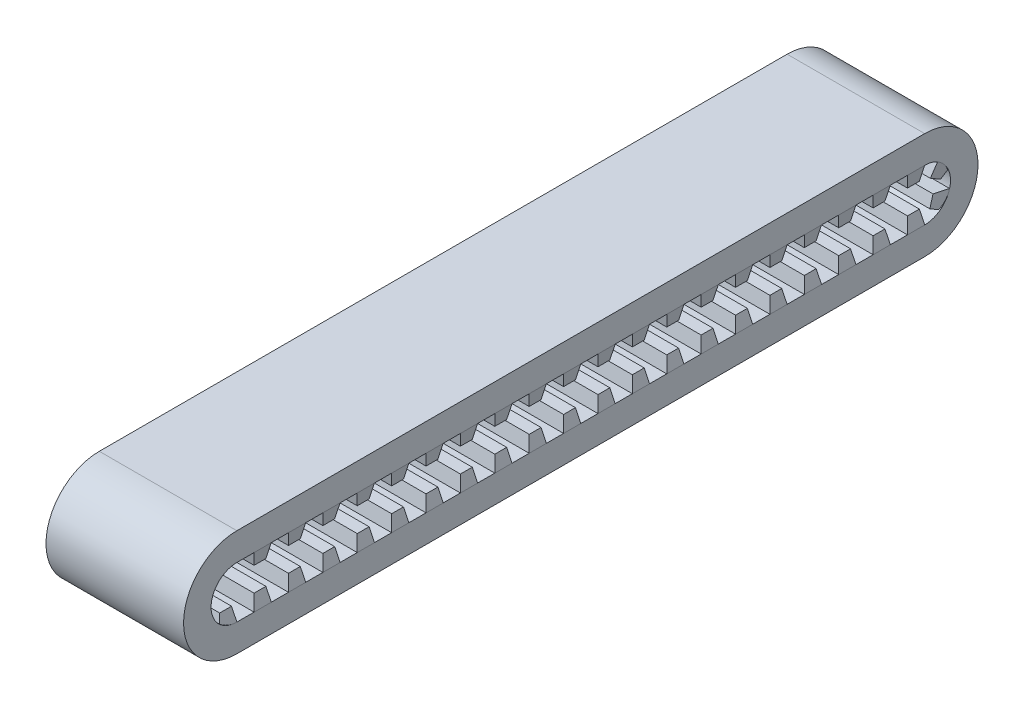
SolidWorks part; units mm, degrees
ref_plane "Front Plane" through (0, 0, 0) normal (0, 0, 1) x (1, 0, 0)
ref_plane "Top Plane" through (0, 0, 0) normal (0, 1, 0) x (1, 0, 0)
ref_plane "Right Plane" through (0, 0, 0) normal (1, 0, 0) x (0, 0, -1)
sketch "Sketch1" plane through (0, 0, 0) normal (1, 0, 0) x (0, 0, -1)
  line L0 (-100, 0) -> (100, 0) construction
  line L1 (-100, 15.5) -> (100, 15.5)
  line L2 (-100, -15.5) -> (100, -15.5)
  line L3 (-100, 0) -> (100, 0) construction
  line L4 (-100, 7.5) -> (100, 7.5)
  line L5 (-100, -7.5) -> (100, -7.5)
  arc A0 (-100, 15.5) -> (-100, -15.5) centre (-100, 0) ccw
  arc A1 (100, -15.5) -> (100, 15.5) centre (100, 0) ccw
  arc A2 (-100, 7.5) -> (-100, -7.5) centre (-100, 0) ccw
  arc A3 (100, -7.5) -> (100, 7.5) centre (100, 0) ccw
  point P2 (0, 0)
  point P10 (0, 0)
  dimension "D1" = 200
  dimension "D2" = 8
  dimension "D3" = 15
extrude "Boss-Extrude1" add sketch "Sketch1" along normal blind 40
sketch "Sketch2" plane through (0, -7.5, 0) normal (0, 1, 0) x (1, 0, 0)
  line L0 (40, 100) -> (40, -100) construction
  line L1 (0, 100) -> (40, 100)
  line L2 (0, 100) -> (0, 95)
  line L3 (0, 95) -> (40, 95)
  line L4 (40, 100) -> (40, 95)
  dimension "D1" = 5
extrude "Boss-Extrude2" add sketch "Sketch2" along normal blind 4 draft 11
pattern_linear "LPattern1" count 19 spacing 10 along (0, 0, 1) of "Boss-Extrude2"
pattern_circular "CirPattern1" count 3 every 75 about axis through (0, 0, -100) along (1, 0, 0) of "Boss-Extrude2"
mirror "Mirror1" about plane through (0, 0, 0) normal (0, 1, 0) of "LPattern1", "Boss-Extrude2"
sketch "Sketch3" plane through (0, -7.5, 0) normal (0, 1, 0) x (1, 0, 0)
  line L0 (0, -100) -> (0, 100) construction
  line L1 (0, -90) -> (40, -90)
  line L2 (0, -90) -> (0, -95)
  line L3 (0, -95) -> (40, -95)
  line L4 (40, -90) -> (40, -95)
  line L5 (40, 100) -> (40, -100) construction
  line L6 (40, 100) -> (0, 100) construction
  dimension "D1" = 5
  dimension "D2" = 190
extrude "Boss-Extrude3" add sketch "Sketch3" along normal blind 4 draft 11
pattern_linear "LPattern2" count 2 spacing 10 along (0, 0, 1) of "Boss-Extrude3"
mirror "Mirror2" about plane through (0, 0, 0) normal (0, 1, 0) of "Boss-Extrude3"
